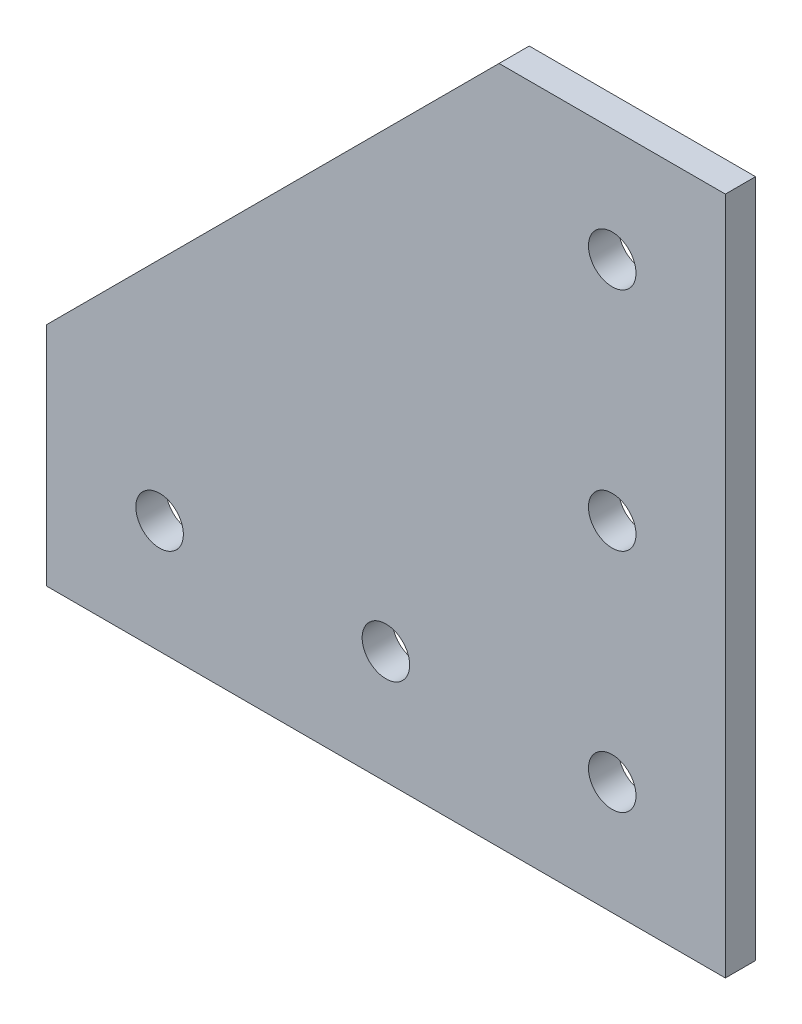
SolidWorks part; units mm, degrees
material "6061 Alloy"
ref_plane "Front Plane" through (0, 0, 0) normal (0, 0, 1) x (1, 0, 0)
ref_plane "Top Plane" through (0, 0, 0) normal (0, 1, 0) x (1, 0, 0)
ref_plane "Right Plane" through (0, 0, 0) normal (1, 0, 0) x (0, 0, -1)
sketch "Sketch1" plane through (0, 0, 0) normal (0, 0, 1) x (1, 0, 0)
  line L0 (14.0154, 97.3157) -> (-15.9846, 97.3157)
  line L1 (-75.9846, 7.3157) -> (-75.9846, 37.3157)
  line L2 (-75.9846, 37.3157) -> (-15.9846, 97.3157)
  line L3 (-75.9846, 7.3157) -> (14.0154, 7.3157)
  line L4 (14.0154, 97.3157) -> (14.0154, 7.3157)
  circle A0 centre (-0.9846, 52.3157) radius 3.15
  circle A1 centre (-0.9846, 82.3157) radius 3.15
  circle A2 centre (-0.9846, 22.3157) radius 3.15
  circle A3 centre (-30.9846, 22.3157) radius 3.15
  circle A4 centre (-60.9846, 22.3157) radius 3.15
  dimension "D1" = 90
  dimension "D2" = 90
extrude "Extrude1" add sketch "Sketch1" along normal blind 4
